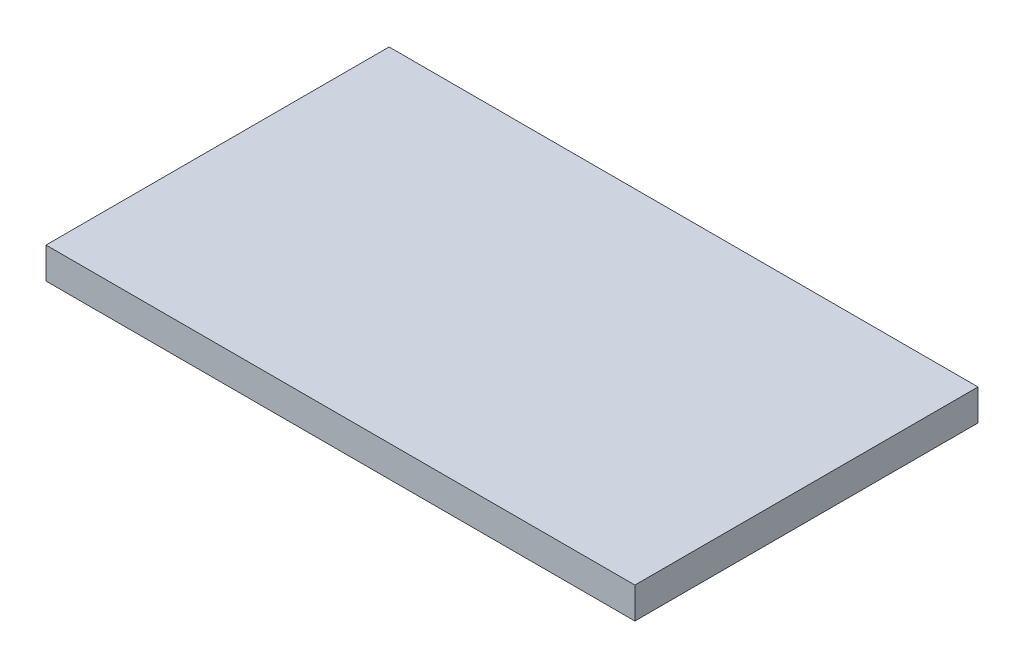
SolidWorks part; units mm, degrees
ref_plane "Front Plane" through (0, 0, 0) normal (0, 0, 1) x (1, 0, 0)
ref_plane "Top Plane" through (0, 0, 0) normal (0, 1, 0) x (1, 0, 0)
ref_plane "Right Plane" through (0, 0, 0) normal (1, 0, 0) x (0, 0, -1)
sketch "Sketch1" plane through (0, 0, 0) normal (1, 0, 0) x (0, 0, -1)
  line L1 (-174.625, 15.875) -> (174.625, 15.875)
  line L2 (-174.625, 15.875) -> (-174.625, -15.875)
  line L3 (-174.625, -15.875) -> (174.625, -15.875)
  line L4 (174.625, 15.875) -> (174.625, -15.875)
  dimension "D1" = 349.25
  dimension "D2" = 31.75
  dimension "D3" = 15.875
  dimension "D4" = 174.625
extrude "Boss-Extrude1" add sketch "Sketch1" along normal mid plane 599.44
